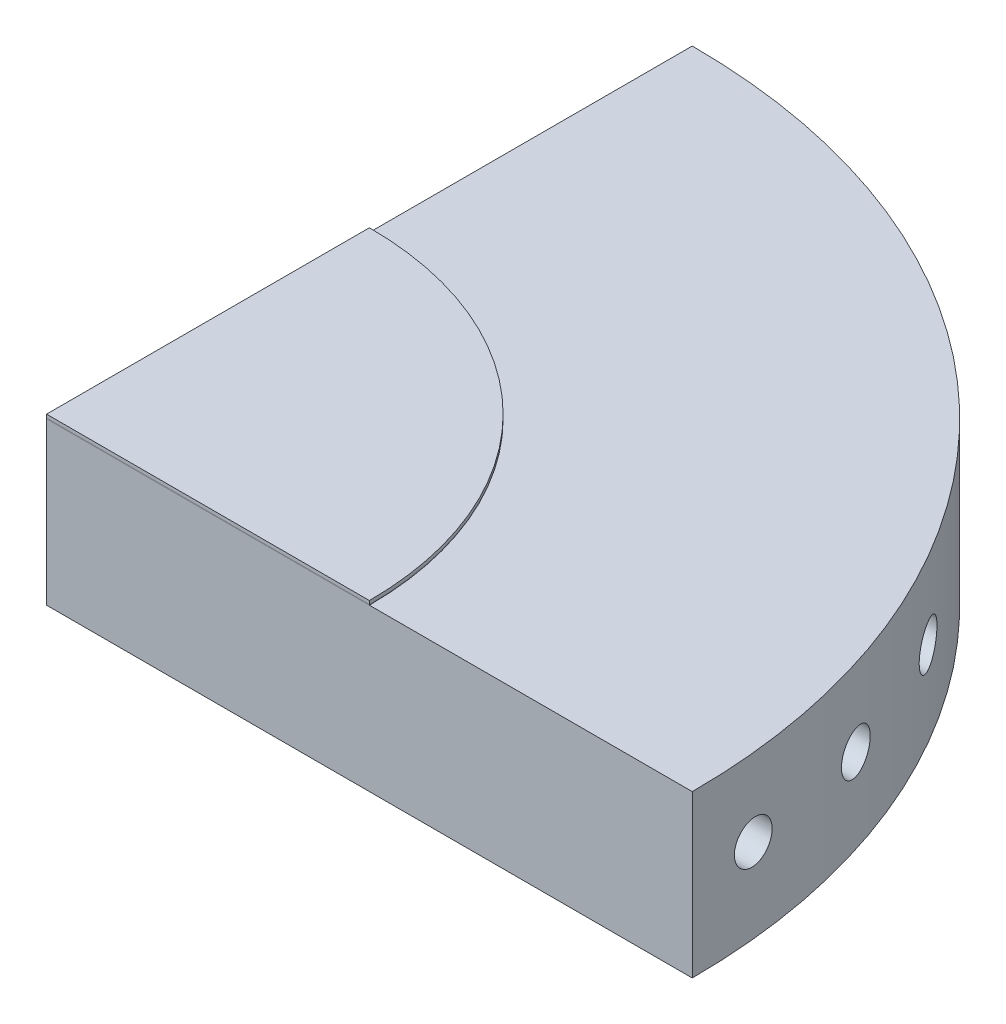
SolidWorks part; units mm, degrees
ref_plane "Front Plane" through (0, 0, 0) normal (0, 0, 1) x (1, 0, 0)
ref_plane "Top Plane" through (0, 0, 0) normal (0, 1, 0) x (1, 0, 0)
ref_plane "Right Plane" through (0, 0, 0) normal (1, 0, 0) x (0, 0, -1)
sketch "Sketch1" plane through (0, 0, 0) normal (0, 1, 0) x (1, 0, 0)
  circle A0 centre (0, 0) radius 100
  dimension "D1" = 200
extrude "Boss-Extrude1" add sketch "Sketch1" along normal blind 25
sketch "Sketch2" plane through (0, 25, 0) normal (0, 1, 0) x (1, 0, 0)
  circle A0 centre (0, 0) radius 50
  dimension "D1" = 100
extrude "Boss-Extrude2" add sketch "Sketch2" along normal blind 0.1 separate body
sketch "Sketch4" plane through (0, 25.1, 0) normal (0, 1, 0) x (1, 0, 0)
  circle A1 centre (0, 0) radius 50
  circle A2 centre (0, 0) radius 50
  dimension "D1" = 0
extrude "Boss-Extrude3" add sketch "Sketch4" along normal blind 0.525 separate body
sketch "Sketch5" plane through (0, 0, 0) normal (1, 0, 0) x (0, 0, -1)
  line L0 (100, 25) -> (-100, 25) construction
  circle A0 centre (10, 13) radius 3.25
  circle A1 centre (30, 13) radius 3.25
  circle A2 centre (50, 13) radius 3.25
  point P9 (0, 0)
  dimension "D1" = 6.5
  dimension "D4" = 6.5
  dimension "D7" = 6.5
  dimension "D2" = 12
  dimension "D3" = 10
  dimension "D5" = 12
  dimension "D6" = 30
  dimension "D8" = 12
  dimension "D9" = 50
extrude "Cut-Extrude1" cut sketch "Sketch5" against normal through all both and the other way through all
sketch "Sketch6" plane through (0, 0, 0) normal (0, -1, 0) x (1, 0, 0)
  circle A0 centre (15, -20) radius 1.5
  circle A1 centre (60, -60) radius 1.5
  point P4 (0, 0)
  point P6 (0, 0)
  dimension "D1" = 3
  dimension "D2" = 3
  dimension "D3" = 20
  dimension "D4" = 15
  dimension "D5" = 60
  dimension "D6" = 60
extrude "Cut-Extrude3" cut sketch "Sketch6" against normal blind 20.5
sketch "Sketch7" plane through (0, 0, 0) normal (0, -1, 0) x (1, 0, 0)
  circle A0 centre (25, -25) radius 3
  point P2 (0, 0)
  dimension "D1" = 6
  dimension "D2" = 25
  dimension "D3" = 25
split line "Split Line1"
sketch "Sketch8" plane through (0, 0, 0) normal (0, -1, 0) x (1, 0, 0)
  line L1 (0, 0) -> (122.6718, 0)
  line L2 (0, 0) -> (0, -113.6482)
  line L11 (0, -113.6482) -> (122.6718, -113.6482)
  line L12 (122.6718, 0) -> (122.6718, -113.6482)
extrude "Cut-Extrude4" cut sketch "Sketch8" against normal through all both and the other way through all flip side to cut
